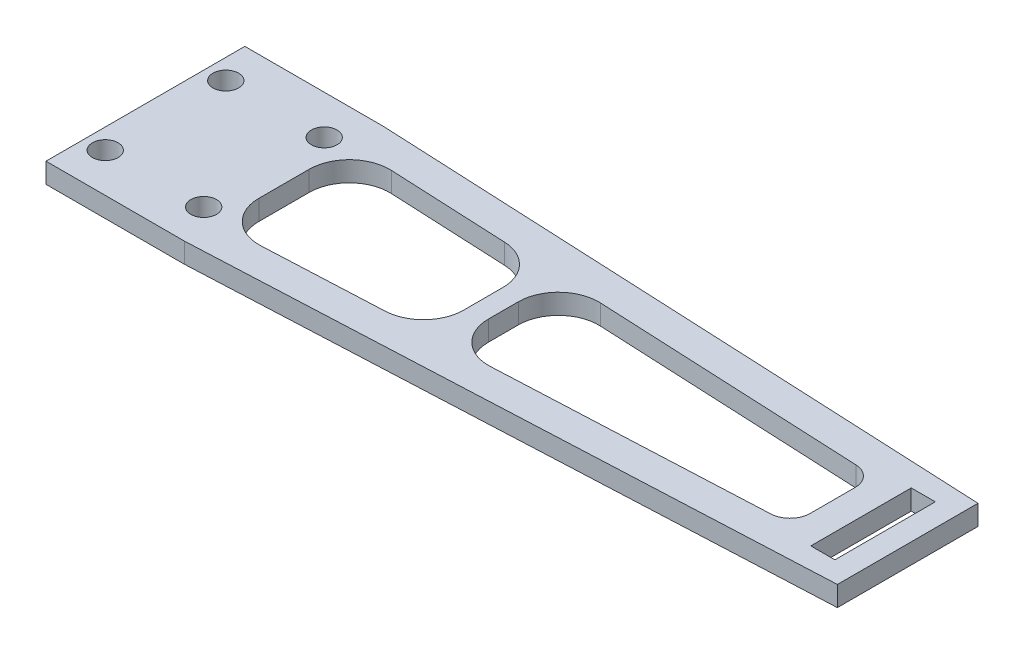
SolidWorks part; units mm, degrees
ref_plane "Front Plane" through (0, 0, 0) normal (0, 0, 1) x (1, 0, 0)
ref_plane "Top Plane" through (0, 0, 0) normal (0, 1, 0) x (1, 0, 0)
ref_plane "Right Plane" through (0, 0, 0) normal (1, 0, 0) x (0, 0, -1)
sketch "Sketch1" plane through (0, 0, 0) normal (0, 1, 0) x (1, 0, 0)
  line L1 (0, 0) -> (34.5, 0)
  line L2 (0, 0) -> (0, 49.5)
  line L3 (0, 49.5) -> (34.5, 49.5)
  line L4 (34.5, 0) -> (34.5, 49.5)
  dimension "D1" = 34.5
  dimension "D2" = 49.5
extrude "Boss-Extrude1" add sketch "Sketch1" along normal blind 5
sketch "Sketch2" plane through (0, 5, 0) normal (0, 1, 0) x (1, 0, 0)
  line L0 (34.5, 49.5) -> (0, 49.5) construction
  line L1 (0, 49.5) -> (0, 0) construction
  line L2 (17.25, 49.5) -> (17.25, 0) construction
  line L3 (0, 0) -> (34.5, 0) construction
  line L4 (0, 24.75) -> (17.25, 24.75) construction
  circle A0 centre (5, 39.75) radius 3.2
  circle A1 centre (5, 9.75) radius 3.2
  circle A2 centre (29.5, 9.75) radius 3.2
  circle A3 centre (29.5, 39.75) radius 3.2
  dimension "D1" = 6.4
  dimension "D3" = 5
  dimension "D2" = 9.75
extrude "Cut-Extrude1" cut sketch "Sketch2" against normal blind 5
sketch "Sketch3" plane through (0, 5, 0) normal (0, 1, 0) x (1, 0, 0)
  line L0 (17.25, 24.75) -> (181.75, 24.75) construction
  line L1 (189.75, 42.25) -> (34.5, 49.5)
  line L2 (189.75, 7.25) -> (34.5, 0)
  line L3 (189.75, 42.25) -> (189.75, 7.25)
  line L4 (171.0535, 14.3856) -> (89.0949, 10.5582)
  line L6 (171.0535, 35.1144) -> (89.0949, 38.9418)
  line L7 (34.5, 49.5) -> (34.5, 41.4913)
  line L8 (34.5, 0) -> (34.5, 49.5) construction
  line L9 (181.75, 34.6149) -> (34.1268, 41.5087) construction
  line L10 (34.5, 0) -> (34.5, 8.0087)
  line L11 (181.75, 14.8851) -> (34.1268, 7.9913) construction
  line L12 (84.0949, 39.1753) -> (84.0949, 10.3247)
  line L13 (89.0949, 38.9418) -> (89.0949, 10.5582)
  line L14 (89.0949, 39.1753) -> (89.0949, 10.3247) construction
  line L16 (0, 49.5) -> (0, 0) construction
  line L17 (0, 0) -> (34.5, 0) construction
  line L18 (84.0949, 39.1753) -> (34.5, 41.4913)
  line L19 (84.0949, 10.3247) -> (34.5, 8.0087)
  line L20 (171.0535, 35.1144) -> (171.0535, 14.3856)
  line L21 (181.75, 34.6149) -> (181.75, 14.8851) construction
  line L22 (178.13, 37.25) -> (184.13, 37.25)
  line L23 (178.13, 37.25) -> (178.13, 12.25)
  line L24 (178.13, 12.25) -> (184.13, 12.25)
  line L25 (184.13, 37.25) -> (184.13, 12.25)
  dimension "D1" = 17.5
  dimension "D4" = 17.25
  dimension "D5" = 24.75
  dimension "D6" = 17.5
  dimension "D7" = 172.5
  dimension "D8" = 25
  dimension "D9" = 12.5
  dimension "D10" = 6
  dimension "D11" = 5.62
  dimension "D2" = 8
  dimension "D3" = 5
extrude "Boss-Extrude2" add sketch "Sketch3" against normal blind 5
sketch "Sketch5" [suppressed] plane through (0, 5, 0) normal (0, 1, 0) x (1, 0, 0)
  line L0 (163.183, 43.1642) -> (163.183, 6.3358)
  line L1 (181.75, 42.25) -> (34.5, 49.5) construction
  line L2 (34.5, 0) -> (181.75, 7.25) construction
  line L3 (163.183, 6.3358) -> (181.75, 7.25)
  line L4 (181.75, 7.25) -> (181.75, 42.25)
  line L5 (181.75, 42.25) -> (163.183, 43.1642)
fillet "Fillet1" radius 10 6 edges at (89.0949, 2.5, -10.5582) (89.0949, 2.5, -38.9418) (84.0949, 2.5, -10.3247) (84.0949, 2.5, -39.1753) (34.5, 2.5, -41.4913) (34.5, 2.5, -8.0087)
fillet "Fillet2" radius 5 2 edges at (171.0535, 2.5, -14.3856) (171.0535, 2.5, -35.1144)
